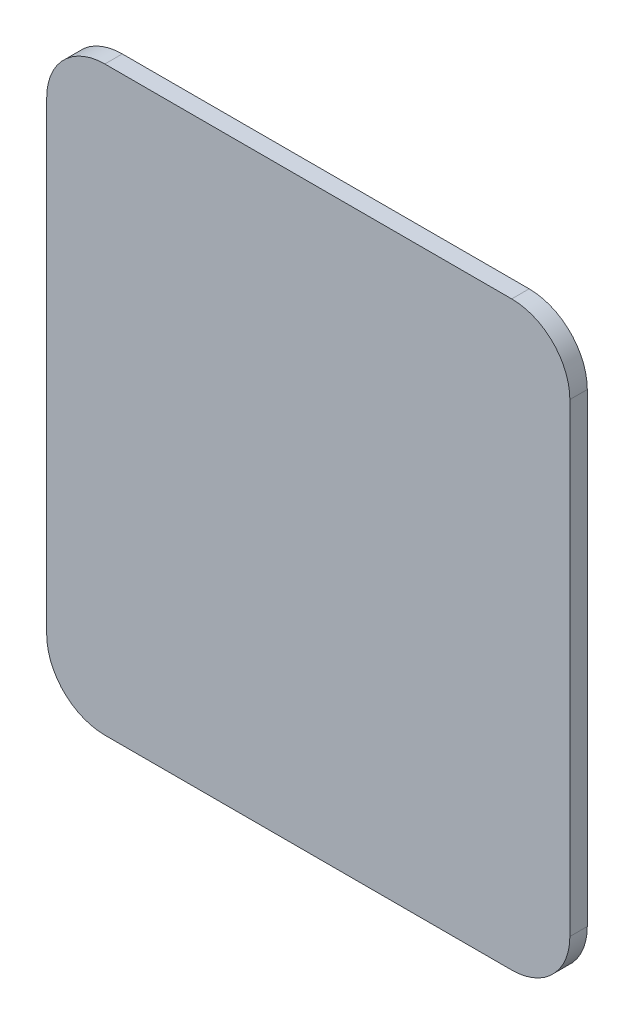
SolidWorks part; units mm, degrees
ref_plane "Front Plane" through (0, 0, 0) normal (0, 0, 1) x (1, 0, 0)
ref_plane "Top Plane" through (0, 0, 0) normal (0, 1, 0) x (1, 0, 0)
ref_plane "Right Plane" through (0, 0, 0) normal (1, 0, 0) x (0, 0, -1)
sketch "Sketch1" plane through (0, 0, 0) normal (0, 0, 1) x (1, 0, 0)
  line L1 (-26.7871, 19.6626) -> (63.2129, 19.6626)
  line L2 (-26.7871, 19.6626) -> (-26.7871, -80.3374)
  line L3 (-26.7871, -80.3374) -> (63.2129, -80.3374)
  line L4 (63.2129, 19.6626) -> (63.2129, -80.3374)
  dimension "D1" = 90
  dimension "D2" = 100
extrude "Boss-Extrude1" add sketch "Sketch1" along normal blind 3
fillet "Fillet1" radius 10 1 edges at (63.2129, 19.6626, 1.5)
fillet "Fillet2" radius 10 1 edges at (-26.7871, 19.6626, 1.5)
fillet "Fillet3" radius 10 1 edges at (-26.7871, -80.3374, 1.5)
fillet "Fillet4" radius 10 1 edges at (63.2129, -80.3374, 1.5)
